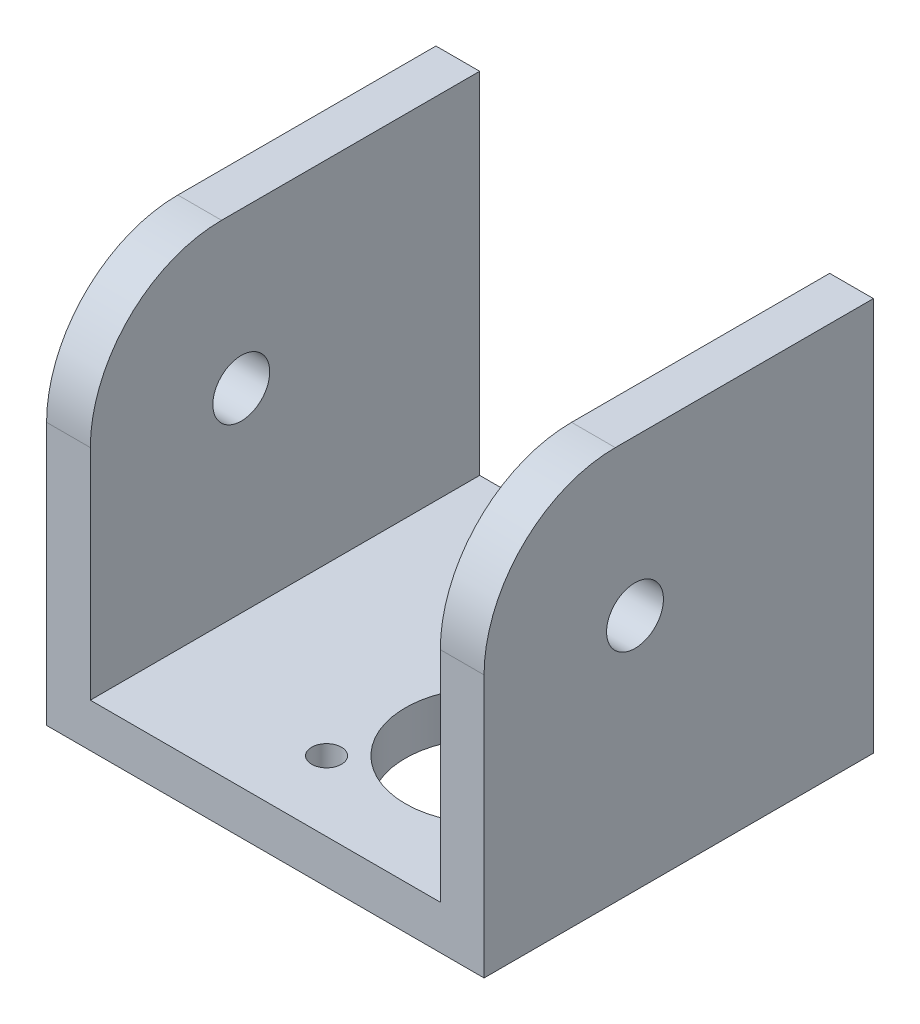
SolidWorks part; units mm, degrees
ref_plane "Plan de face" through (0, 0, 0) normal (0, 0, 1) x (1, 0, 0)
ref_plane "Plan de dessus" through (0, 0, 0) normal (0, 1, 0) x (1, 0, 0)
ref_plane "Plan de droite" through (0, 0, 0) normal (1, 0, 0) x (0, 0, -1)
sketch "Esquisse1" plane through (0, 0, 0) normal (0, 0, 1) x (1, 0, 0)
  line L1 (0, 0) -> (50, 0)
  line L2 (0, 0) -> (0, 45)
  line L3 (0, 45) -> (50, 45)
  line L4 (50, 0) -> (50, 45)
  dimension "D1" = 50
  dimension "D2" = 45
extrude "Boss.-Extru.1" add sketch "Esquisse1" along normal blind 44.5
sketch "Esquisse2" plane through (0, 0, 44.5) normal (0, 0, 1) x (1, 0, 0)
  line L4 (50, 45) -> (0, 45) construction
  line L5 (45, 45) -> (5, 45)
  line L8 (5, 40) -> (5, 5)
  line L9 (5, 5) -> (45, 5)
  line L10 (45, 5) -> (45, 40)
  line L11 (45, 40) -> (5, 40)
  line L12 (5, 45) -> (5, 5)
  line L13 (5, 5) -> (45, 5)
  line L14 (45, 5) -> (45, 45)
  dimension "D1" = 5
extrude "Enlèv. mat.-Extru.1" cut sketch "Esquisse2" against normal up to surface (44.5 mm away) up to face at (25, 22.5, 0)
sketch "Esquisse3" plane through (0, 5, 0) normal (0, 1, 0) x (1, 0, 0)
  line L0 (5, -44.5) -> (45, -44.5) construction
  line L1 (50, -44.5) -> (50, 0) construction
  line L3 (42.5, -18) -> (24, -18) construction
  line L4 (42.5, -18) -> (42.5, -36.5) construction
  line L5 (42.5, -36.5) -> (24, -36.5) construction
  line L6 (24, -18) -> (24, -36.5) construction
  circle A0 centre (33.25, -27.25) radius 9.5
  circle A2 centre (42.5, -18) radius 1.5
  circle A3 centre (24, -18) radius 1.5
  circle A4 centre (24, -36.5) radius 1.5
  circle A5 centre (42.5, -36.5) radius 1.5
  point P14 (33.25, -18)
  point P15 (36.0275, -27.25)
  point P16 (0, 0)
  point P17 (42.5, -18.1447)
  point P18 (42.5, -27.25)
  dimension "D1" = 19
  dimension "D5" = 3
  dimension "D9" = 3
  dimension "D10" = 3
  dimension "D11" = 3
  dimension "D2" = 17.25
  dimension "D3" = 16.75
  dimension "D7" = 18.5
  dimension "D8" = 18.5
extrude "Enlèv. mat.-Extru.2" cut sketch "Esquisse3" against normal up to surface (5 mm away) up to face at (25, 0, 22.25)
hole_wizard "Dégagement M31" positions "Esquisse4" profile "Esquisse6" hole size "M3" standard "ISO" end condition through all
sketch "Esquisse4" plane through (0, 5, 0) normal (0, 1, 0) x (1, 0, 0)
  point P0 (42.5, -18)
  point P3 (24, -18)
  point P6 (24, -36.5)
  point P9 (42.5, -36.5)
sketch "Esquisse6" plane through (42.5, 5, 18) normal (1, 0, 0) x (0, 0, 1)
  line L0 (0, 0) -> (0, 5)
  line L1 (0, 5) -> (1.7, 5)
  line L2 (1.7, 5) -> (1.7, 0)
  line L5 (1.7, 0) -> (0, 0)
  line L11 (0, -6.35) -> (0, 107.95) construction
  dimension "Diamètre du perçage jusqu'au prochain" = 3.4
  dimension "Profondeur du perçage jusqu'au prochain" = 5
pattern_circular "Répétition circulaire1" [suppressed] count 4 over 360
fillet "Congé1" radius 15 2 edges at (2.5, 45, 44.5) (47.5, 45, 44.5)
sketch "Esquisse7" plane through (50, 0, 0) normal (1, 0, 0) x (0, 0, -1)
  line L0 (-44.5, 0) -> (0, 0) construction
  line L1 (0, 0) -> (0, 45) construction
  circle A0 centre (-27.25, 27.25) radius 3.25
  dimension "D1" = 6.5
  dimension "D2" = 27.25
  dimension "D3" = 27.25
extrude "Enlèv. mat.-Extru.3" cut sketch "Esquisse7" against normal up to surface (50 mm away) up to face at (0, 24.6213, 24.3213)
equation "\"D8@Esquisse3\"=\"D7@Esquisse3\""
equation "\"D2@Esquisse7\"=24+\"D1@Esquisse7\"/2"
equation "\"D3@Esquisse7\"=\"D2@Esquisse7\""
